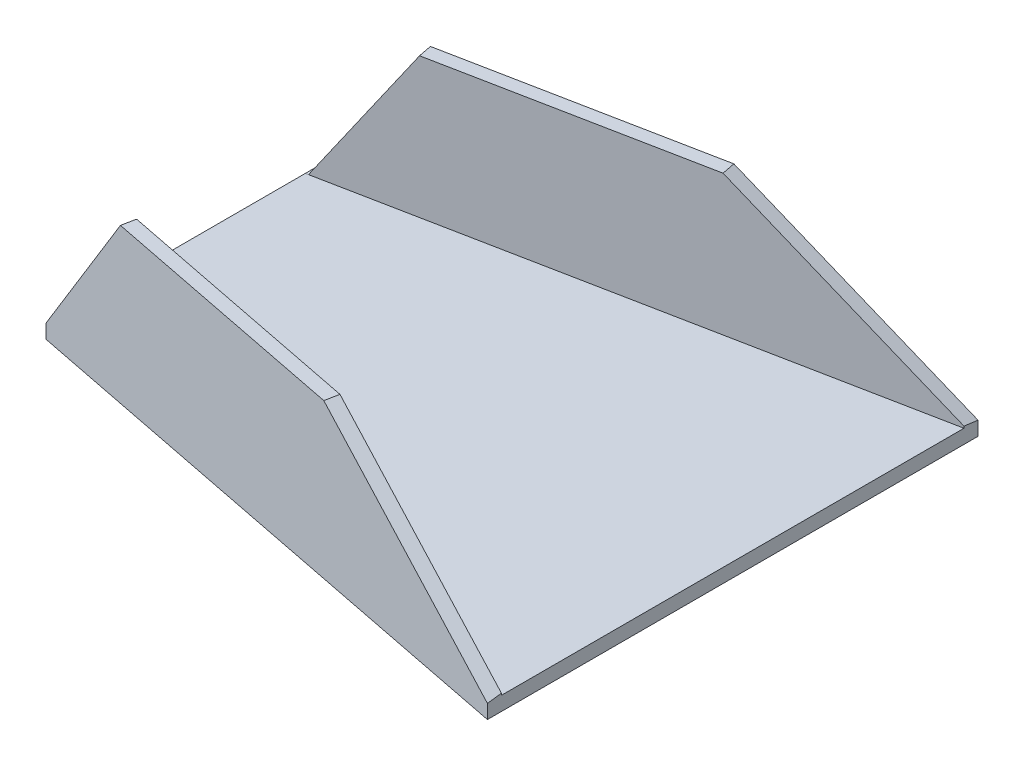
SolidWorks part; units mm, degrees
ref_plane "Front Plane" through (0, 0, 0) normal (0, 0, 1) x (1, 0, 0)
ref_plane "Top Plane" through (0, 0, 0) normal (0, 1, 0) x (1, 0, 0)
ref_plane "Right Plane" through (0, 0, 0) normal (1, 0, 0) x (0, 0, -1)
sketch "Sketch1" plane through (0, 0, 0) normal (0, 1, 0) x (1, 0, 0)
  line L0 (0, 0) -> (0, -39)
  line L1 (0, -39) -> (78.4841, -54.5)
  line L2 (78.4841, -54.5) -> (78.4841, 15.5)
  line L3 (78.4841, 15.5) -> (0, 0)
  dimension "D1" = 80
  dimension "D2" = 80
  dimension "D3" = 70
  dimension "D4" = 39
extrude "Boss-Extrude1" add sketch "Sketch1" along normal blind 2
sketch "Sketch2" plane through (0, 2, 0) normal (0, 1, 0) x (1, 0, 0)
  line L0 (0, -39) -> (78.4841, -54.5)
  line L1 (78.4841, -54.5) -> (78.4841, -52.5)
  line L2 (78.4841, -54.5) -> (78.4841, 15.5) construction
  line L3 (78.4841, -52.5) -> (0, -37)
  line L4 (0, 0) -> (0, -39) construction
  line L5 (0, -37) -> (0, -39)
  line L6 (0, -19.5) -> (78.4841, -19.5) construction
  line L7 (78.4841, 15.5) -> (78.4841, 13.5)
  line L9 (0, 0) -> (78.4841, 15.5)
  line L10 (78.4841, 13.5) -> (0, -2)
  line L11 (0, -2) -> (0, 0)
  dimension "D1" = 2
extrude "Boss-Extrude2" add sketch "Sketch2" along normal blind 20
sketch "Sketch3" plane through (-7.4131, 0, 37.536) normal (-0.1938, 0, 0.9811) x (0.9811, 0, 0.1938)
  line L0 (21.0464, 22) -> (2.1568, 22)
  line L1 (7.5563, 22) -> (87.5563, 22) construction
  line L2 (2.1568, 22) -> (2.1568, 2)
  line L3 (2.1568, 2) -> (7.5563, 2)
  line L4 (7.5563, 22) -> (7.5563, 0) construction
  line L5 (7.5563, 2) -> (21.0464, 22)
  line L6 (7.5563, 0) -> (87.5563, 0) construction
  dimension "D1" = 56
  dimension "D2" = 20
extrude "Cut-Extrude6" cut sketch "Sketch3" against normal blind 5
sketch "Sketch4" plane through (0, 0, 0) normal (-0.1937, 0, -0.9811) x (-0.9811, 0, 0.1937)
  line L0 (-13.49, 22) -> (7.9718, 22)
  line L1 (-80, 22) -> (0, 22) construction
  line L2 (7.9718, 22) -> (7.9718, 2.0003)
  line L3 (7.9718, 2.0003) -> (0, 2.0003)
  line L4 (0, 22) -> (0, 0) construction
  line L5 (0, 2.0003) -> (-13.49, 22)
  line L6 (-80, 0) -> (0, 0) construction
  dimension "D1" = 56
extrude "Cut-Extrude7" cut sketch "Sketch4" against normal blind 5
sketch "Sketch6" plane through (-7.4131, 0, 37.536) normal (-0.1938, 0, 0.9811) x (0.9811, 0, 0.1938)
  line L0 (57.905, 22) -> (98.624, 22)
  line L1 (21.0464, 22) -> (87.5563, 22) construction
  line L2 (98.624, 22) -> (98.624, 2)
  line L3 (98.624, 2) -> (87.5563, 2)
  line L4 (87.5563, 22) -> (87.5563, 0) construction
  line L5 (87.5563, 2) -> (57.905, 22)
  line L6 (7.5563, 0) -> (87.5563, 0) construction
  dimension "D1" = 20
  dimension "D2" = 34
extrude "Cut-Extrude8" cut sketch "Sketch6" against normal blind 5
sketch "Sketch7" plane through (0, 0, 0) normal (-0.1937, 0, -0.9811) x (-0.9811, 0, 0.1937)
  line L0 (-50.3488, 22) -> (-88.9818, 22)
  line L1 (-80, 22) -> (-13.49, 22) construction
  line L2 (-88.9818, 22) -> (-88.9818, 2)
  line L3 (-88.9818, 2) -> (-80, 2)
  line L4 (-80, 22) -> (-80, 0) construction
  line L5 (-80, 2) -> (-50.3488, 22)
  line L6 (-80, 0) -> (0, 0) construction
  dimension "D1" = 20
  dimension "D2" = 34
extrude "Cut-Extrude9" cut sketch "Sketch7" against normal blind 5
